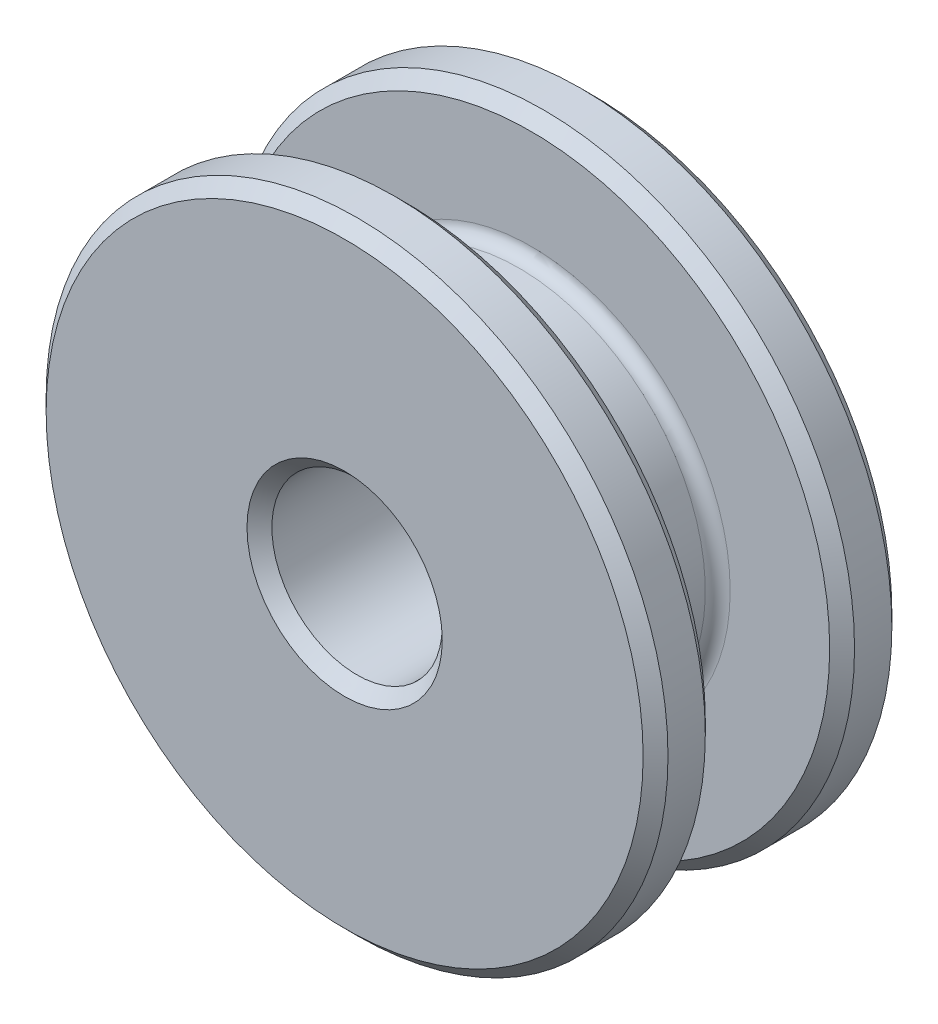
SolidWorks part; units mm, degrees
material "Nylon 101"
ref_plane "Front" through (0, 0, 0) normal (0, 0, 1) x (1, 0, 0)
ref_plane "Top" through (0, 0, 0) normal (0, 1, 0) x (1, 0, 0)
ref_plane "Right" through (0, 0, 0) normal (1, 0, 0) x (0, 0, -1)
sketch "Sketch1" plane through (0, 0, 0) normal (0, 0, 1) x (1, 0, 0)
  circle A1 centre (0, 0) radius 12.5
  circle A3 centre (0, 0) radius 3.175 construction
  circle A4 centre (0, 0) radius 3.425
  dimension "D1" = 6.35
  dimension "D3" = 25
  dimension "D2" = 0.25
extrude "Boss-Extrude1" add sketch "Sketch1" along normal blind 10
sketch "Sketch2" plane through (0, 0, 0) normal (0, 1, 0) x (1, 0, 0)
  line L0 (-12.5, -2.5) -> (-12.5, -7.5)
  line L1 (-12.5, 0) -> (-12.5, -10) construction
  line L2 (-12.5, -7.5) -> (-7.5, -7.5)
  line L3 (-7.5, -7.5) -> (-7.5, -2.5)
  line L4 (-7.5, -2.5) -> (-12.5, -2.5)
  line L5 (0, 0) -> (0, -10) construction
  line L6 (12.5, 0) -> (-12.5, 0) construction
  line L7 (-12.5, -10) -> (12.5, -10) construction
  line L8 (0, -5) -> (-0.788, -5) construction
  dimension "D1" = 5
  dimension "D2" = 5
revolve "Cut-Revolve1" cut sketch "Sketch2" angle 360 about L5
chamfer "Chamfer1" distance 0.5 angle 45 6 edges at (12.5, 0, 0) (-12.5, 0, 2.5) (-12.5, 0, 7.5) (12.5, 0, 10) (3.425, 0, 0) (3.425, 0, 10)
fillet "Fillet1" radius 0.5 2 edges at (-7.5, 0, 7.5) (-7.5, 0, 2.5)
